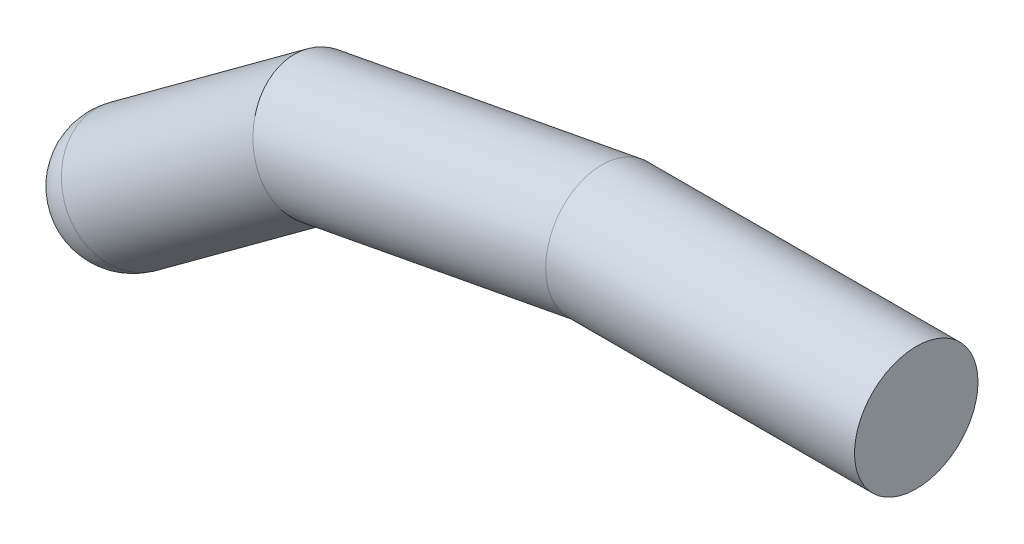
SolidWorks part; units mm, degrees
ref_plane "Front Plane" through (0, 0, 0) normal (0, 0, 1) x (1, 0, 0)
ref_plane "Top Plane" through (0, 0, 0) normal (0, 1, 0) x (1, 0, 0)
ref_plane "Right Plane" through (0, 0, 0) normal (1, 0, 0) x (0, 0, -1)
sketch "Sketch1" plane through (0, 0, 0) normal (0, 0, 1) x (1, 0, 0)
  line L0 (0, 0) -> (-20, 0)
  line L1 (-20, 0) -> (-38.6705, -3.5231)
  line L2 (-38.6705, -3.5231) -> (-53.9803, -14.7752)
  dimension "D1" = 20
  dimension "D2" = 19
  dimension "D3" = 19
sketch "Sketch2" plane through (0, 0, 0) normal (1, 0, 0) x (0, 0, -1)
  circle A0 centre (0, 0) radius 4
  dimension "D1" = 8
sweep "Sweep1" add profiles "Sketch2" path "Sketch1"
fillet "Fillet1" radius 4 1 edges at (-53.9803, -14.7752, -4)
